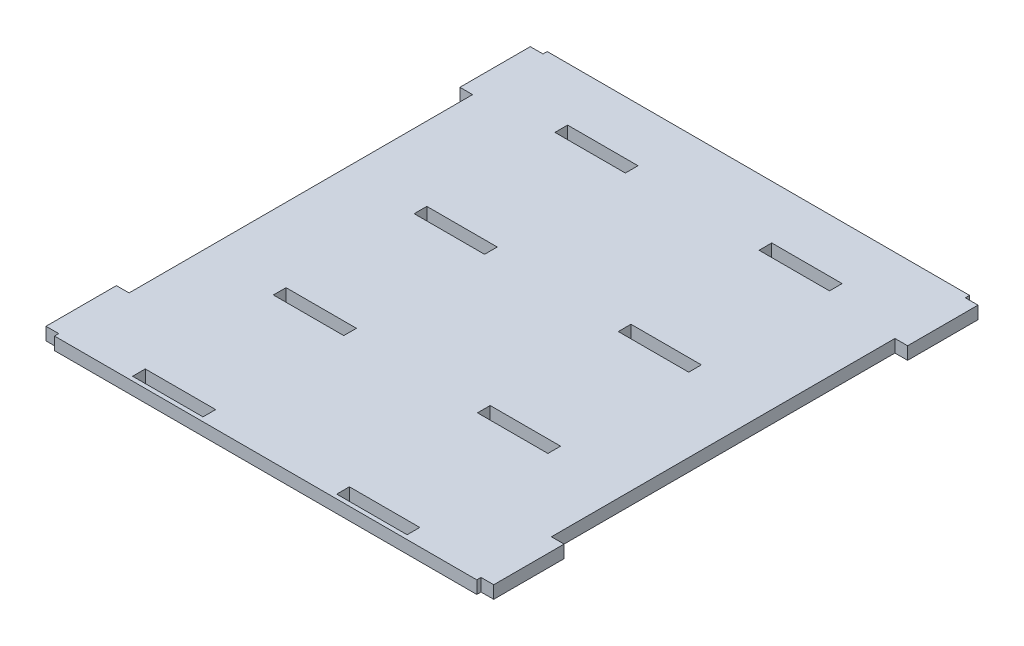
SolidWorks part; units mm, degrees
ref_plane "Front Plane" through (0, 0, 0) normal (0, 0, 1) x (1, 0, 0)
ref_plane "Top Plane" through (0, 0, 0) normal (0, 1, 0) x (1, 0, 0)
ref_plane "Right Plane" through (0, 0, 0) normal (1, 0, 0) x (0, 0, -1)
sketch "Sketch1" plane through (0, 0, 0) normal (0, 1, 0) x (1, 0, 0)
  line L0 (-300, -7.1119) -> (300, -7.1119)
  line L1 (300, -7.1119) -> (300, -13.1119)
  line L2 (300, -13.1119) -> (318, -13.1119)
  line L3 (318, -13.1119) -> (318, -113.1119)
  line L4 (318, -113.1119) -> (300, -113.1119)
  line L5 (-318, -113.1119) -> (-300, -113.1119)
  line L6 (-300, -701.1119) -> (-200.3776, -701.1119)
  line L7 (-300, -701.1119) -> (-300, -674.1404) construction
  line L8 (-195, -701.1119) -> (-95, -701.1119)
  line L9 (-318, -13.1119) -> (-318, -113.1119)
  line L10 (-300, -13.1119) -> (-318, -13.1119)
  line L11 (-300, -7.1119) -> (-300, -13.1119)
  line L12 (300, -7.1119) -> (300, -13.1119)
  line L13 (300, -13.1119) -> (318, -13.1119)
  line L14 (318, -13.1119) -> (318, -113.1119)
  line L15 (318, -113.1119) -> (300, -113.1119)
  line L16 (-318, -113.1119) -> (-300, -113.1119)
  line L17 (-318, -13.1119) -> (-318, -113.1119)
  line L18 (-300, -13.1119) -> (-318, -13.1119)
  line L19 (-300, -7.1119) -> (-300, -13.1119)
  line L20 (-300, -707.1119) -> (-300, -701.1119)
  line L21 (-300, -701.1119) -> (-318, -701.1119)
  line L22 (-318, -701.1119) -> (-318, -601.1119)
  line L23 (-318, -601.1119) -> (-300, -601.1119)
  line L24 (318, -601.1119) -> (300, -601.1119)
  line L25 (318, -701.1119) -> (318, -601.1119)
  line L26 (300, -701.1119) -> (318, -701.1119)
  line L27 (300, -707.1119) -> (300, -701.1119)
  line L28 (-300, -707.1119) -> (-300, -701.1119)
  line L29 (-300, -701.1119) -> (-318, -701.1119)
  line L30 (-318, -701.1119) -> (-318, -601.1119)
  line L31 (-318, -601.1119) -> (-300, -601.1119)
  line L32 (318, -601.1119) -> (300, -601.1119)
  line L33 (318, -701.1119) -> (318, -601.1119)
  line L34 (300, -701.1119) -> (318, -701.1119)
  line L35 (300, -707.1119) -> (300, -701.1119)
  line L36 (-300, -707.1119) -> (300, -707.1119)
  line L37 (-300, -113.1119) -> (-300, -601.1119)
  line L38 (300, -113.1119) -> (300, -601.1119)
  line L39 (-195, -701.1119) -> (-195, -683.1119)
  line L40 (-195, -683.1119) -> (-95, -683.1119)
  line L41 (-95, -701.1119) -> (-95, -683.1119)
  line L42 (0, -707.1119) -> (0, 0) construction
  line L43 (195, -701.1119) -> (195, -683.1119)
  line L44 (95, -701.1119) -> (95, -683.1119)
  line L45 (195, -683.1119) -> (95, -683.1119)
  line L46 (195, -701.1119) -> (95, -701.1119)
  line L47 (195, -483.1119) -> (95, -483.1119)
  line L48 (195, -501.1119) -> (195, -483.1119)
  line L49 (195, -501.1119) -> (95, -501.1119)
  line L50 (95, -501.1119) -> (95, -483.1119)
  line L51 (-95, -501.1119) -> (-95, -483.1119)
  line L52 (-195, -483.1119) -> (-95, -483.1119)
  line L53 (-195, -501.1119) -> (-95, -501.1119)
  line L54 (-195, -501.1119) -> (-195, -483.1119)
  line L55 (195, -283.1119) -> (95, -283.1119)
  line L56 (195, -301.1119) -> (195, -283.1119)
  line L57 (195, -301.1119) -> (95, -301.1119)
  line L58 (95, -301.1119) -> (95, -283.1119)
  line L59 (-95, -301.1119) -> (-95, -283.1119)
  line L60 (-195, -283.1119) -> (-95, -283.1119)
  line L61 (-195, -301.1119) -> (-95, -301.1119)
  line L62 (-195, -301.1119) -> (-195, -283.1119)
  line L63 (195, -83.1119) -> (95, -83.1119)
  line L64 (195, -101.1119) -> (195, -83.1119)
  line L65 (195, -101.1119) -> (95, -101.1119)
  line L66 (95, -101.1119) -> (95, -83.1119)
  line L67 (-95, -101.1119) -> (-95, -83.1119)
  line L68 (-195, -83.1119) -> (-95, -83.1119)
  line L69 (-195, -101.1119) -> (-95, -101.1119)
  line L70 (-195, -101.1119) -> (-195, -83.1119)
  dimension "D1" = 6
  dimension "D2" = 100
  dimension "D3" = 100
  dimension "D4" = 18
  dimension "D5" = 6
  dimension "D6" = 18
  dimension "D7" = 6
  dimension "D8" = 105
  dimension "D9" = 4
extrude "Boss-Extrude1" add sketch "Sketch1" along normal blind 18
